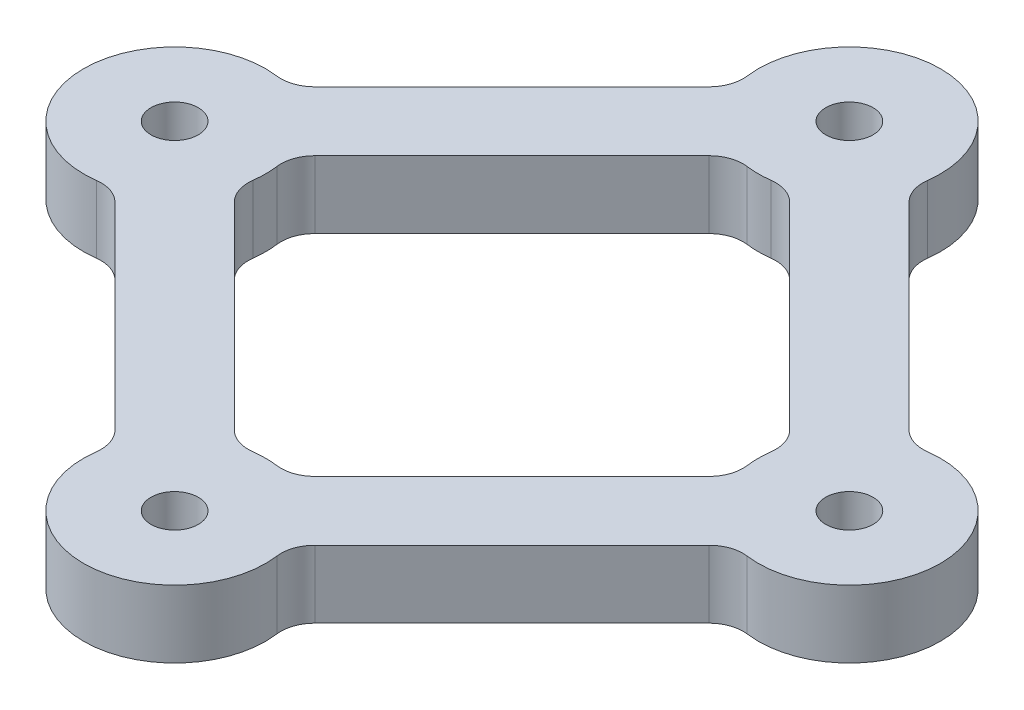
SolidWorks part; units mm, degrees
ref_plane "Front Plane" through (0, 0, 0) normal (0, 0, 1) x (1, 0, 0)
ref_plane "Top Plane" through (0, 0, 0) normal (0, 1, 0) x (1, 0, 0)
ref_plane "Right Plane" through (0, 0, 0) normal (1, 0, 0) x (0, 0, -1)
sketch "Sketch1" plane through (0, 0, 0) normal (0, 1, 0) x (1, 0, 0)
  line L0 (0, 10) -> (0, 0)
  line L1 (0, 10) -> (-10, 0)
  line L2 (-10, 0) -> (0, -10)
  line L3 (0, -10) -> (10, 0)
  line L4 (10, 0) -> (0, 10)
  circle A0 centre (0, 0) radius 10 construction
  dimension "D1" = 20
sketch "Sketch2" plane through (0, 0, 0) normal (0, 1, 0) x (1, 0, 0)
  line L1 (-2.5761, 9.1916) -> (-9.1916, 2.5761)
  line L2 (-2.5761, 9.1916) -> (-0.8084, 7.4239)
  line L3 (-9.1916, 2.5761) -> (-7.4239, 0.8084)
  line L4 (-0.8084, 7.4239) -> (-7.4239, 0.8084)
  line L5 (-2.5761, 9.1916) -> (-7.4239, 0.8084) construction
  line L6 (-9.1916, 2.5761) -> (-0.8084, 7.4239) construction
  line L7 (2.5761, 9.1916) -> (9.1916, 2.5761)
  line L8 (2.5761, 9.1916) -> (0.8084, 7.4239)
  line L9 (9.1916, 2.5761) -> (7.4239, 0.8084)
  line L10 (0.8084, 7.4239) -> (7.4239, 0.8084)
  line L11 (2.5761, 9.1916) -> (7.4239, 0.8084) construction
  line L12 (9.1916, 2.5761) -> (0.8084, 7.4239) construction
  line L13 (-9.1916, -2.5761) -> (-2.5761, -9.1916)
  line L14 (-9.1916, -2.5761) -> (-7.4239, -0.8084)
  line L15 (-2.5761, -9.1916) -> (-0.8084, -7.4239)
  line L16 (-7.4239, -0.8084) -> (-0.8084, -7.4239)
  line L17 (-9.1916, -2.5761) -> (-0.8084, -7.4239) construction
  line L18 (-2.5761, -9.1916) -> (-7.4239, -0.8084) construction
  line L19 (0.8084, -7.4239) -> (7.4239, -0.8084)
  line L20 (0.8084, -7.4239) -> (2.5761, -9.1916)
  line L21 (7.4239, -0.8084) -> (9.1916, -2.5761)
  line L22 (2.5761, -9.1916) -> (9.1916, -2.5761)
  line L23 (0.8084, -7.4239) -> (9.1916, -2.5761) construction
  line L24 (7.4239, -0.8084) -> (2.5761, -9.1916) construction
  circle A5 centre (0, 10) radius 0.7
  circle A6 centre (0, 10) radius 2.7
  circle A9 centre (-10, 0) radius 0.7
  circle A10 centre (-10, 0) radius 2.7
  circle A11 centre (0, -10) radius 0.7
  circle A12 centre (0, -10) radius 2.7
  circle A13 centre (10, 0) radius 0.7
  circle A14 centre (10, 0) radius 2.7
  point P14 (5, 5)
  point P16 (-5, 5)
  point P28 (-5, -5)
  point P33 (5, -5)
  dimension "D1" = 1.4
  dimension "D2" = 2
  dimension "D3" = 2.5
extrude "Boss-Extrude1" add sketch "Sketch2" along normal blind 2 contours L14 A10 L3 A9 | A10 L4 A6 L1 | L8 A6 L2 A5 | A14 L7 A6 L10 | L9 A14 L21 A13 | A14 L19 A12 L22 | L20 A12 L15 A11 | A12 L16 A10 L13 | L14 A10 | L3 A10 | L2 A6 | L8 A6 | L9 A14 | L21 A14 | L20 A12 | L15 A12
fillet "Fillet1" radius 1 16 edges at (-2.5761, 1, 9.1916) (-9.1916, 1, -2.5761) (-2.5761, 1, -9.1916) (2.5761, 1, -9.1916) (9.1916, 1, -2.5761) (9.1916, 1, 2.5761) (2.5761, 1, 9.1916) (-0.8084, 1, -7.4239) (-7.4239, 1, -0.8084) (-7.4239, 1, 0.8084) (-0.8084, 1, 7.4239) (0.8084, 1, 7.4239) (7.4239, 1, 0.8084) (7.4239, 1, -0.8084) (0.8084, 1, -7.4239) (-9.1916, 1, 2.5761)
